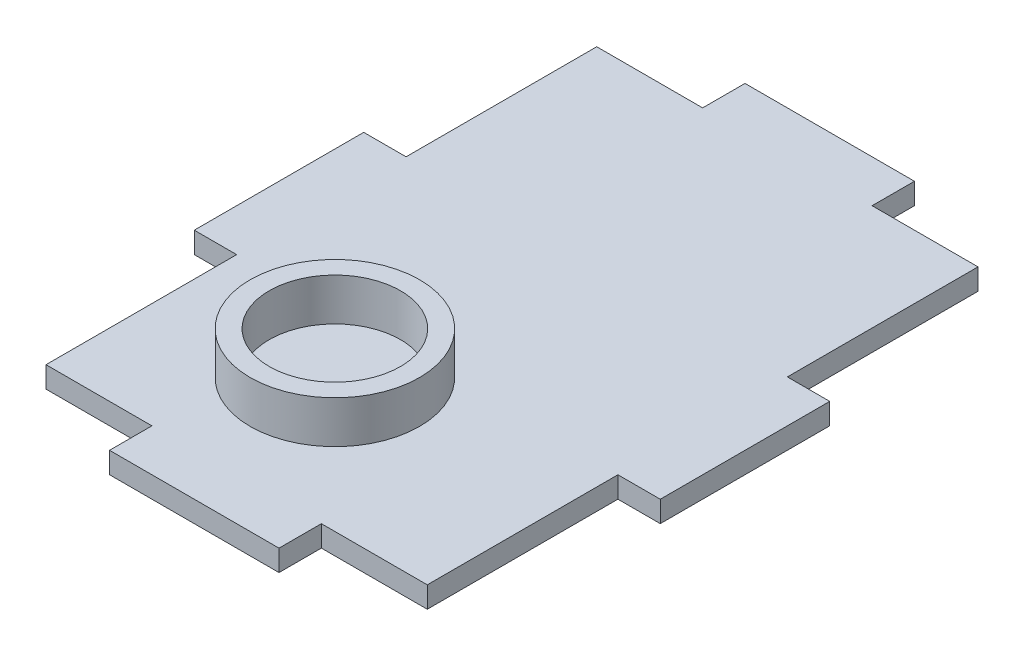
SolidWorks part; units mm, degrees
ref_plane "Front Plane" through (0, 0, 0) normal (0, 0, 1) x (1, 0, 0)
ref_plane "Top Plane" through (0, 0, 0) normal (0, 1, 0) x (1, 0, 0)
ref_plane "Right Plane" through (0, 0, 0) normal (1, 0, 0) x (0, 0, -1)
sketch "Sketch1" plane through (0, 0, 0) normal (0, 1, 0) x (1, 0, 0)
  line L1 (0, 0) -> (90, 0)
  line L2 (0, 0) -> (0, 130)
  line L3 (0, 130) -> (90, 130)
  line L4 (90, 0) -> (90, 130)
  line L5 (0, 85) -> (-10, 85)
  line L6 (0, 85) -> (0, 45)
  line L7 (0, 45) -> (-10, 45)
  line L8 (-10, 85) -> (-10, 45)
  line L9 (25, 130) -> (65, 130)
  line L10 (25, 130) -> (25, 140)
  line L11 (25, 140) -> (65, 140)
  line L12 (65, 130) -> (65, 140)
  line L13 (90, 85) -> (100, 85)
  line L14 (90, 85) -> (90, 45)
  line L15 (90, 45) -> (100, 45)
  line L16 (100, 85) -> (100, 45)
  line L17 (65, 0) -> (25, 0)
  line L18 (65, 0) -> (65, -10)
  line L19 (65, -10) -> (25, -10)
  line L20 (25, 0) -> (25, -10)
  point P21 (45, -10)
  point P22 (45, 140)
  point P23 (45, 0)
  point P24 (45, 130)
  point P25 (100, 65)
  point P26 (-10, 65)
  point P27 (90, 65)
  dimension "D1" = 90
  dimension "D2" = 130
  dimension "D3" = 10
  dimension "D4" = 10
  dimension "D5" = 10
  dimension "D6" = 10
  dimension "D7" = 40
  dimension "D8" = 40
  dimension "D9" = 40
  dimension "D10" = 40
extrude "Boss-Extrude1" add sketch "Sketch1" along normal blind 5 contours L1 L4 L3 L2 | L5 L8 L7 L2 | L16 L13 L4 L15 | L1 L20 L19 L18 | L11 L12 L9 L10
sketch "Sketch4" plane through (0, 5, 0) normal (0, 1, 0) x (1, 0, 0)
  line L0 (0, 0) -> (0, 45) construction
  line L1 (65, 0) -> (90, 0) construction
  circle A0 centre (36.72, 31.47) radius 31.25
  circle A1 centre (36.72, 31.47) radius 15.5
  circle A2 centre (36.72, 31.47) radius 20
  dimension "D3" = 62.5
  dimension "D4" = 31
  dimension "D5" = 40
  dimension "D1" = 36.72
  dimension "D2" = 31.47
extrude "Boss-Extrude2" add sketch "Sketch4" along normal blind 10 contours A2 A1
equation "\"D4@Sketch4\"=15.5*2"
